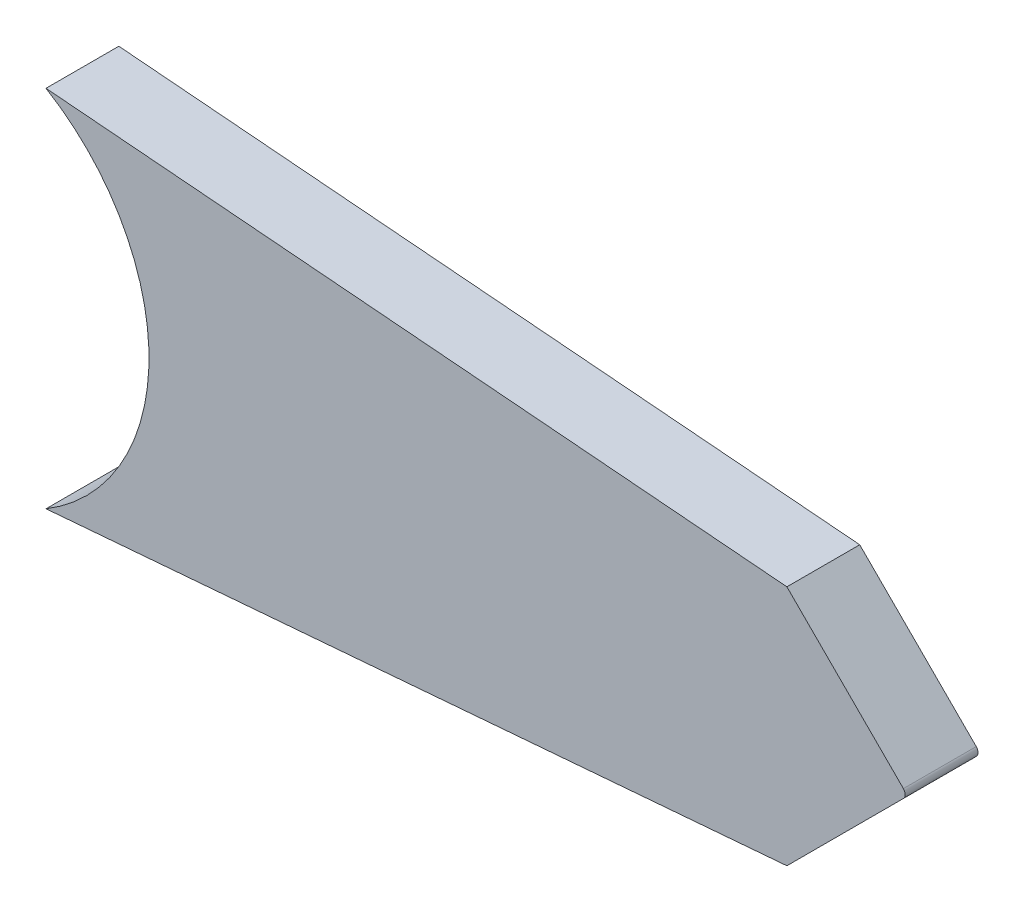
SolidWorks part; units mm, degrees
material "ASTM A36 Steel"
ref_plane "Front Plane" through (0, 0, 0) normal (0, 0, 1) x (1, 0, 0)
ref_plane "Top Plane" through (0, 0, 0) normal (0, 1, 0) x (1, 0, 0)
ref_plane "Right Plane" through (0, 0, 0) normal (1, 0, 0) x (0, 0, -1)
sketch "Sketch1" plane through (0, 0, 0) normal (0, 0, 1) x (1, 0, 0)
  line L0 (51.0832, -19.9018) -> (-70.9872, -30)
  line L1 (-70.9872, 30) -> (51.0832, 19.9018)
  line L2 (51.0832, 19.9018) -> (70.985, 0)
  line L3 (70.985, 0) -> (51.0832, -19.9018)
  arc A0 (-70.9872, 30) -> (-70.9872, -30) centre (-89.015, 0) cw
  dimension "D2" = 35
  dimension "D1" = 141.9722
  dimension "D3" = 39.8037
  dimension "D4" = 28.1455
  dimension "D5" = 122.4874
  dimension "D6" = 122.4874
  dimension "D7" = 18.0278
  dimension "D8" = 70.985
  dimension "D9" = 30
extrude "Boss-Extrude1" add sketch "Sketch1" along normal mid plane 12
fillet "Fillet1" radius 1 1 edges at (70.985, 0, 0)
